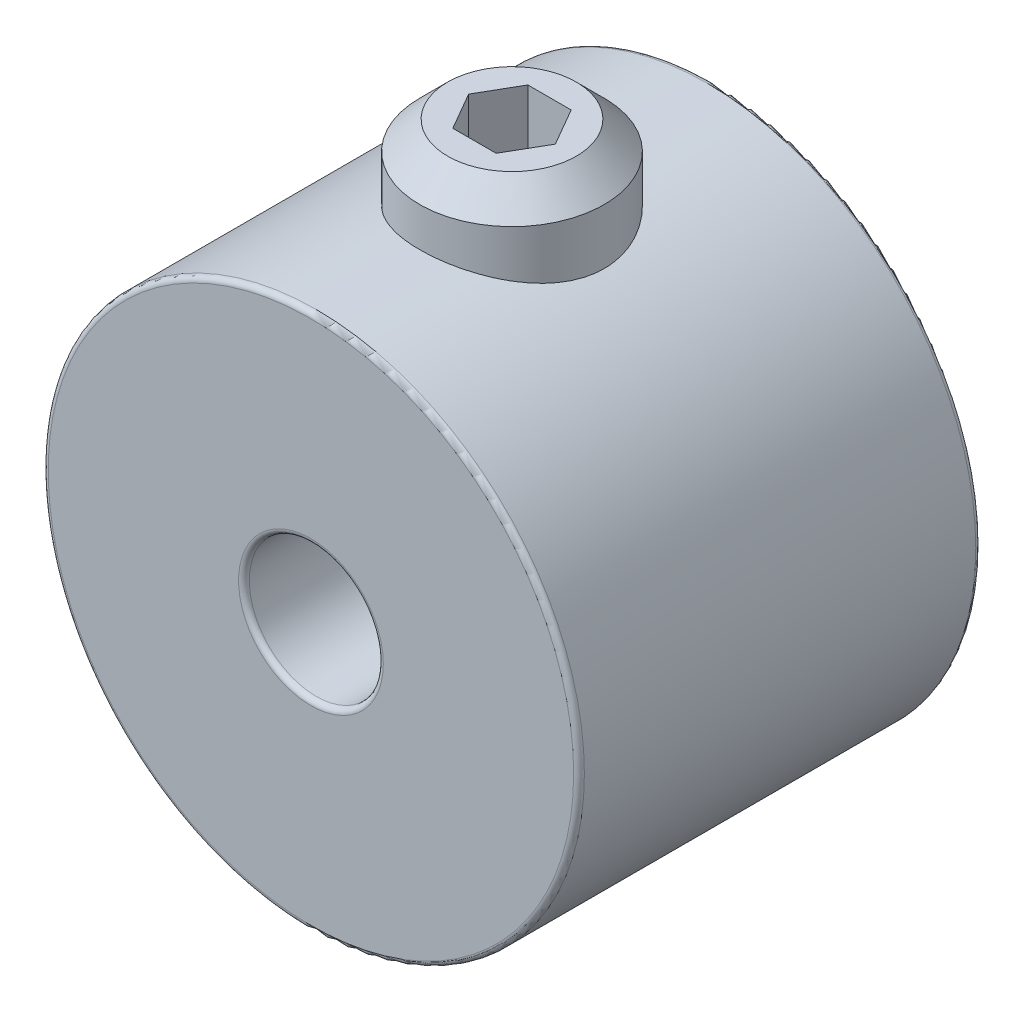
SolidWorks part; units mm, degrees
ref_plane "Front Plane" through (0, 0, 0) normal (0, 0, 1) x (1, 0, 0)
ref_plane "Top Plane" through (0, 0, 0) normal (0, 1, 0) x (1, 0, 0)
ref_plane "Right Plane" through (0, 0, 0) normal (1, 0, 0) x (0, 0, -1)
sketch "Sketch1" plane through (0, 0, 0) normal (0, 0, 1) x (1, 0, 0)
  circle A0 centre (0, 0) radius 3.175
  circle A1 centre (0, 0) radius 0.7937
  point P4 (3.175, 0)
  dimension "Bore Dia" = 1.5875
  dimension "OD" = 6.35
extrude "Extrude1" add sketch "Sketch1" along normal mid plane 4.7625
sketch "Sketch2" plane through (41.275, 0, 0) normal (0, -1, 0) x (0, 0, -1)
  line L0 (2.3812, -41.275) -> (-2.3813, -41.275) construction
  line L1 (-2.3813, -38.1) -> (-2.3813, -44.45) construction
  line L2 (2.3813, -44.45) -> (2.3813, -38.1) construction
  circle A0 centre (0, -41.275) radius 1.0922
  point P7 (0, -42.3672)
  dimension "Set Screw Dia" = 2.1844
extrude "Cut-Extrude1" cut sketch "Sketch2" against normal through all
fillet "Fillet1" radius 0.0635 4 edges at (0.7937, 0, -2.3813) (0.7937, 0, 2.3813) (3.175, 0, -2.3813) (3.175, 0, 2.3813)
sketch "Sketch3" plane through (0, 0, 0) normal (0, 0, 1) x (1, 0, 0)
  line L0 (-0.7614, 0.7937) -> (-0.397, 0.7937)
  line L1 (0, 1.1907) -> (-0.397, 0.7937)
  line L2 (0, 1.1907) -> (0, 3.9688)
  line L3 (0, 3.9688) -> (-0.7614, 3.9688)
  line L4 (-1.0922, 1.1246) -> (-1.0922, 3.6379)
  line L5 (0, 0.7937) -> (0, 0) construction
  line L6 (-1.0922, 1.1246) -> (-1.0922, 0.7937) construction
  line L7 (-1.0922, 0.7937) -> (-0.7614, 0.7937) construction
  line L8 (-1.0922, 3.6379) -> (-1.0922, 3.9688) construction
  line L9 (-0.7614, 0.7937) -> (-1.0922, 1.1246)
  line L10 (-1.0922, 3.6379) -> (-0.7614, 3.9688)
  line L11 (-1.0922, 3.9688) -> (-0.7614, 3.9688) construction
  line L12 (-0.397, 0.7937) -> (0, 0.7937) construction
  line L13 (0, 0.7937) -> (0, 1.1907) construction
  circle A1 centre (0, 0) radius 0.7937 construction
  dimension "Screw Length" = 3.175
  dimension "D2" = 0.3308
  dimension "D1" = 0.397
revolve "Revolve1" add sketch "Sketch3" angle 360 about L5
sketch "Sketch4" plane through (3.3734, 3.9687, 0) normal (0, -1, 0) x (0, 0, -1)
  line L1 (0, -2.8602) -> (-0.4445, -3.1168)
  line L2 (-0.4445, -3.1168) -> (-0.4445, -3.6301)
  line L3 (-0.4445, -3.6301) -> (0, -3.8867)
  line L4 (0, -3.8867) -> (0.4445, -3.6301)
  line L5 (0.4445, -3.6301) -> (0.4445, -3.1168)
  line L6 (0.4445, -3.1168) -> (0, -2.8602)
  circle A0 centre (0, -3.3734) radius 0.4445 construction
  circle A1 centre (0, -3.3734) radius 0.5133 construction
  dimension "Hex Size" = 0.889
extrude "Cut-Extrude2" cut sketch "Sketch4" along normal blind 0.889
equation "\"D1@Fillet1\" = \"OD@Sketch1\"*.01"
equation "\"D1@Cut-Extrude2\" = \"Hex Size@Sketch4\""
equation "\"D2@Sketch3\" =(\"Set Screw Dia@Sketch2\"-\"D1@Sketch4\")/3.5"
equation "\"D1@Sketch3\" = \"D2@Sketch3\"*1.2"
